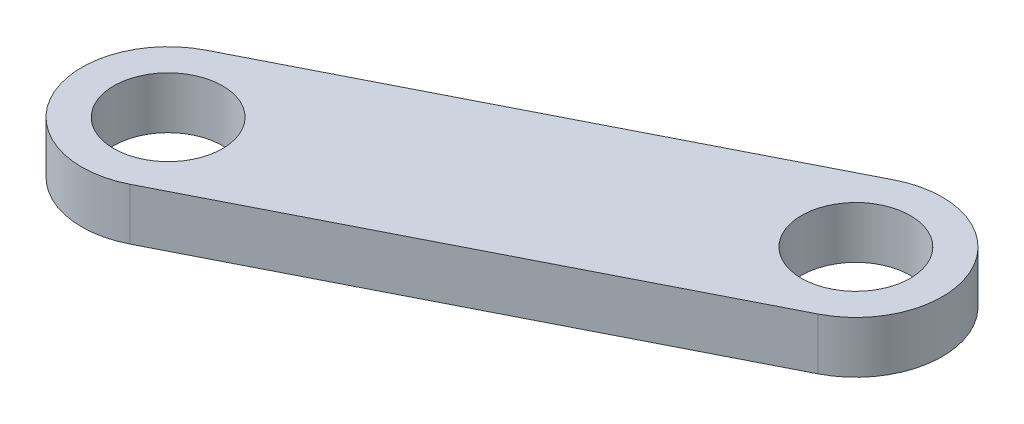
SolidWorks part; units mm, degrees
material "6061-T6 (SS)"
ref_plane "X-Y Datum" through (0, 0, 0) normal (0, 0, 1) x (1, 0, 0)
ref_plane "X-Z Datum" through (0, 0, 0) normal (0, 1, 0) x (1, 0, 0)
ref_plane "Y-Z Datum" through (0, 0, 0) normal (1, 0, 0) x (0, 0, -1)
sketch "Sketch1" plane through (0, 0, 0) normal (0, 1, 0) x (1, 0, 0)
  line L4 (0, 0) -> (-16.764, 0) construction
  line L5 (-16.764, 0) -> (-16.764, -8.509) construction
  line L6 (-16.764, -8.509) -> (0, 0) construction
  line L7 (1.437, -2.8312) -> (-15.327, -11.3402)
  line L8 (-1.437, 2.8312) -> (-18.201, -5.6778)
  line L9 (1.437, -2.8312) -> (-1.437, 2.8312) construction
  circle A4 centre (0, 0) radius 2
  arc A5 (1.437, -2.8312) -> (-1.437, 2.8312) centre (0, 0) ccw
  arc A6 (-15.327, -11.3402) -> (-18.201, -5.6778) centre (-16.764, -8.509) cw
  circle A7 centre (-16.764, -8.509) radius 2
  dimension "D1" = 4
  dimension "D4" = 6.35
  dimension "D2" = 16.764
  dimension "D5" = 4
  dimension "D3" = 8.509
extrude "Boss-Extrude1" add sketch "Sketch1" against normal blind 1.905
